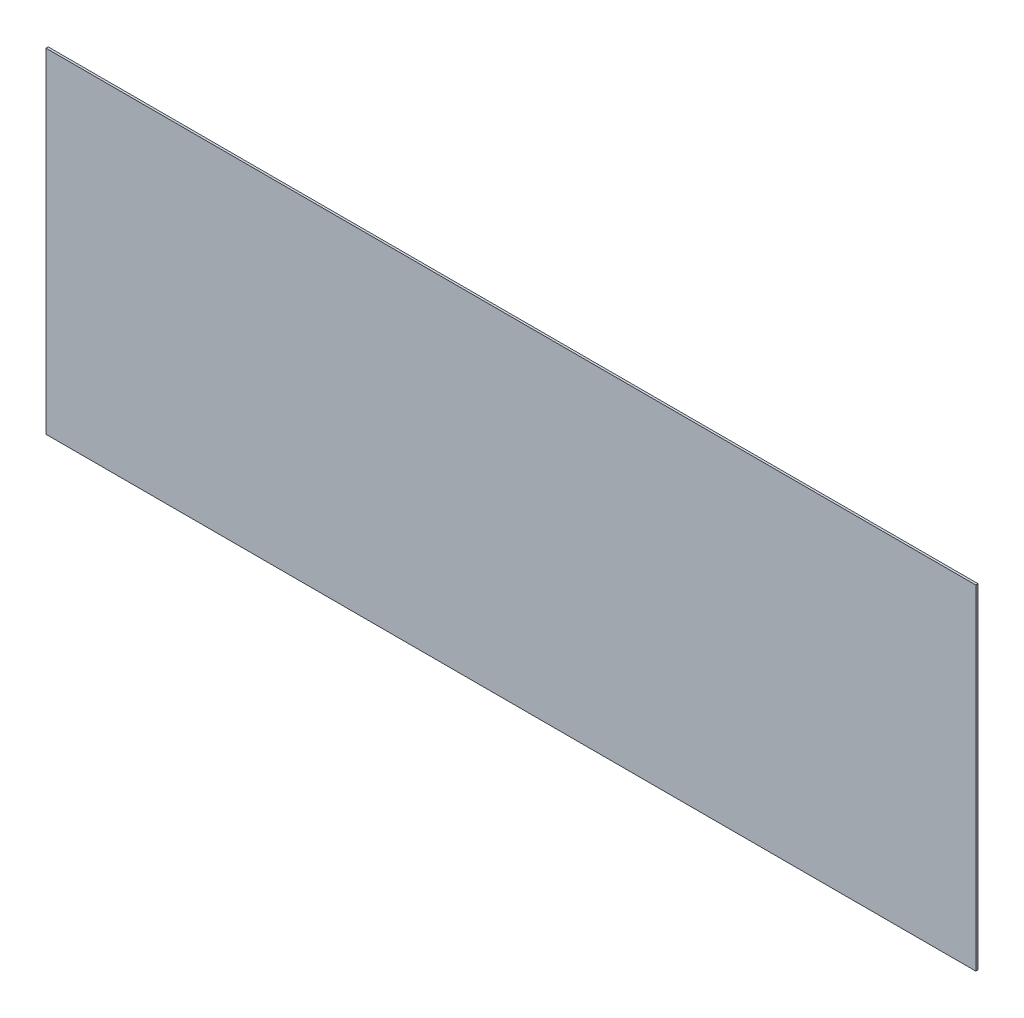
SolidWorks part; units mm, degrees
ref_plane "Front Plane" through (0, 0, 0) normal (0, 0, 1) x (1, 0, 0)
ref_plane "Top Plane" through (0, 0, 0) normal (0, 1, 0) x (1, 0, 0)
ref_plane "Right Plane" through (0, 0, 0) normal (1, 0, 0) x (0, 0, -1)
sketch "Sketch2" plane through (0, 0, 0) normal (0, 0, 1) x (1, 0, 0)
  line L1 (0, 0) -> (620, 0)
  line L2 (0, 0) -> (0, 223)
  line L3 (0, 223) -> (620, 223)
  line L4 (620, 0) -> (620, 223)
  dimension "D1" = 223
  dimension "D2" = 620
extrude "Boss-Extrude1" add sketch "Sketch2" along normal blind 1.5
